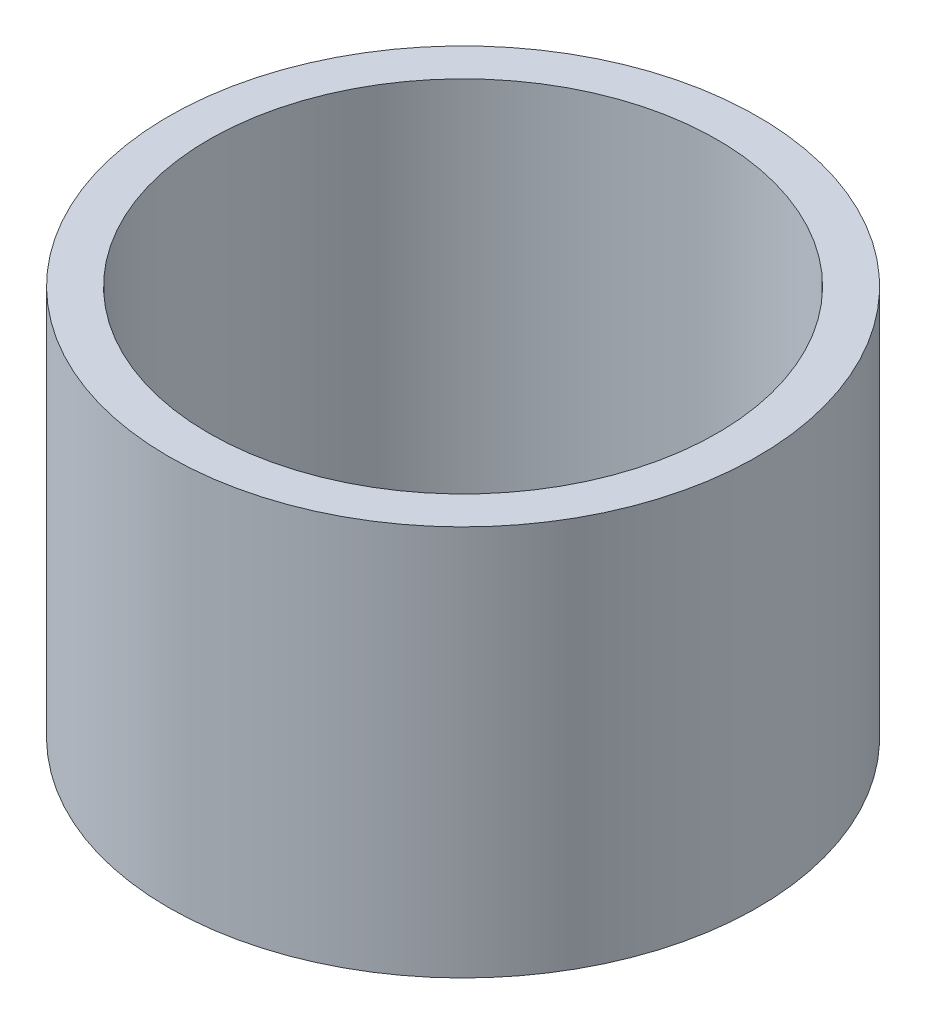
SolidWorks part; units mm, degrees
ref_plane "Front Plane" through (0, 0, 0) normal (0, 0, 1) x (1, 0, 0)
ref_plane "Top Plane" through (0, 0, 0) normal (0, 1, 0) x (1, 0, 0)
ref_plane "Right Plane" through (0, 0, 0) normal (1, 0, 0) x (0, 0, -1)
sketch "Sketch1" plane through (0, 0, 0) normal (0, 1, 0) x (1, 0, 0)
  circle A0 centre (0, 0) radius 4.75
  circle A1 centre (0, 0) radius 4.1
  point P5 (0, 0)
  point P6 (0.0792, -0.1219)
  dimension "D1" = 9.5
  dimension "D2" = 8.2
extrude "Boss-Extrude1" add sketch "Sketch1" along normal blind 6.3
